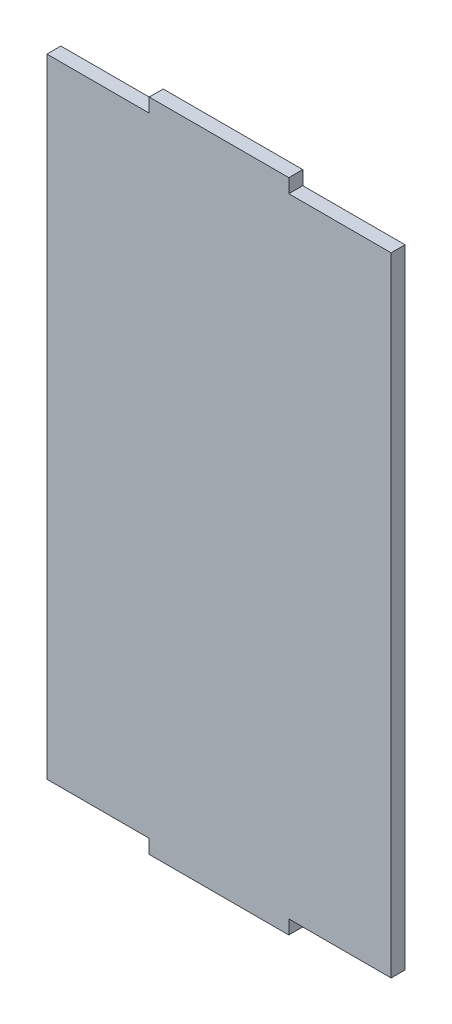
SolidWorks part; units mm, degrees
material "Teca"
ref_plane "Plano frontal" through (0, 0, 0) normal (0, 0, 1) x (1, 0, 0)
ref_plane "Plano superior" through (0, 0, 0) normal (0, 1, 0) x (1, 0, 0)
ref_plane "Plano direito" through (0, 0, 0) normal (1, 0, 0) x (0, 0, -1)
sketch "Esboço1" plane through (0, 0, 0) normal (0, 0, 1) x (1, 0, 0)
  line L0 (52, 0) -> (74, 0)
  line L17 (0, 0) -> (22, 0)
  line L18 (0, 0) -> (0, 135)
  line L19 (0, 135) -> (22, 135)
  line L20 (74, 0) -> (74, 135)
  line L22 (22, 0) -> (22, -3)
  line L23 (22, -3) -> (52, -3)
  line L24 (52, 0) -> (52, -3)
  line L26 (22, 135) -> (22, 138)
  line L27 (22, 138) -> (52, 138)
  line L28 (52, 135) -> (52, 138)
  line L29 (52, 135) -> (74, 135)
  dimension "D1" = 135
  dimension "D2" = 30
  dimension "D3" = 22
  dimension "D4" = 74
  dimension "D5" = 3
  dimension "D6" = 30
  dimension "D7" = 3
  dimension "D8" = 22
extrude "Ressalto-extrusão1" add sketch "Esboço1" along normal blind 3
